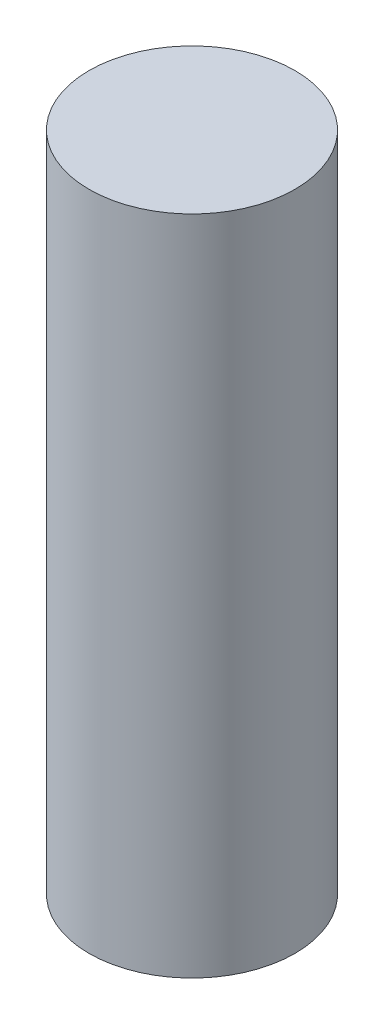
SolidWorks part; units mm, degrees
ref_plane "前视基准面" through (0, 0, 0) normal (0, 0, 1) x (1, 0, 0)
ref_plane "上视基准面" through (0, 0, 0) normal (0, 1, 0) x (1, 0, 0)
ref_plane "右视基准面" through (0, 0, 0) normal (1, 0, 0) x (0, 0, -1)
other "Configuration Table"
sketch "草图1" plane through (0, 0, 0) normal (0, 1, 0) x (1, 0, 0)
  circle A0 centre (0, 0) radius 1.4
  point P0 (-90.6464, 22.0667)
  dimension "D1" = 2.8
extrude "凸台-拉伸1" add sketch "草图1" along normal blind 9
